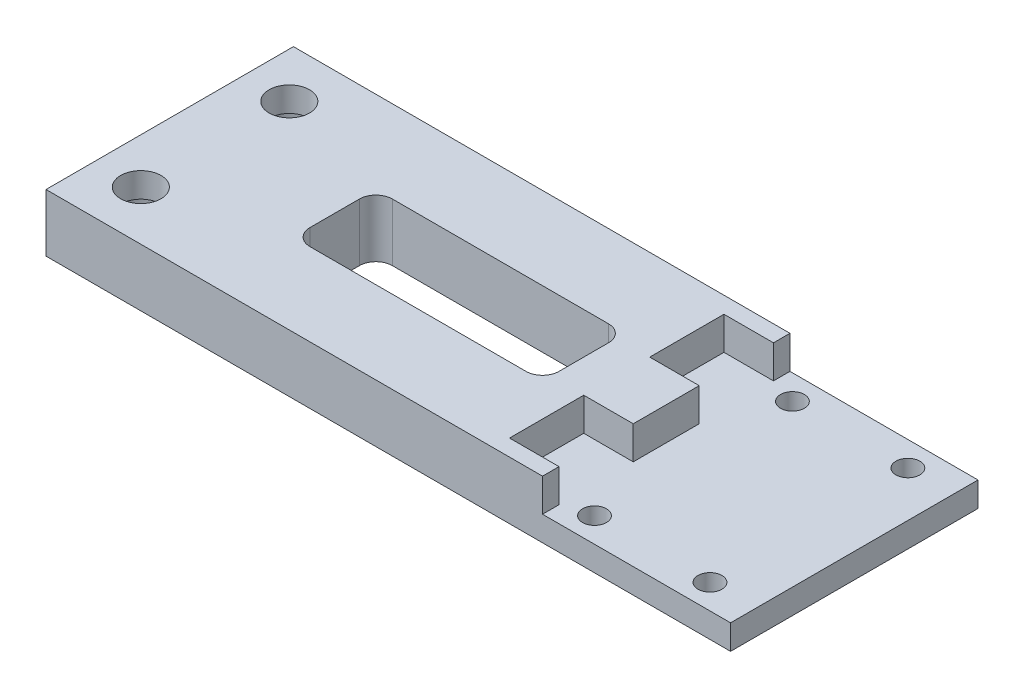
SolidWorks part; units mm, degrees
other "标注1"
sketch "草图16" plane through (-5, 0, 0) normal (0.1182, -0.9126, 0.3914) x (-0.9865, -0.0628, 0.1513)
ref_plane "前视基准面" through (0, 0, 0) normal (0, 0, 1) x (1, 0, 0)
ref_plane "上视基准面" through (0, 0, 0) normal (0, 1, 0) x (1, 0, 0)
ref_plane "右视基准面" through (0, 0, 0) normal (1, 0, 0) x (0, 0, -1)
other "Configuration Table"
sketch "草图1" plane through (0, 0, 0) normal (0, 1, 0) x (1, 0, 0)
  line L1 (0, 0) -> (-88, 0)
  line L2 (0, 0) -> (0, 30)
  line L3 (0, 30) -> (-88, 30)
  line L4 (-88, 0) -> (-88, 30)
  dimension "D1" = 88
  dimension "D2" = 30
extrude "凸台-拉伸1" add sketch "草图1" along normal blind 3
sketch "草图2" plane through (0, 3, 0) normal (0, 1, 0) x (1, 0, 0)
  line L0 (-88, 0) -> (0, 0) construction
  line L1 (0, 30) -> (-27.8, 30)
  line L2 (0, 30) -> (0, 0)
  line L3 (0, 0) -> (-27.8, 0)
  line L4 (-27.8, 30) -> (-27.8, 0)
  dimension "D1" = 27.8
extrude "切除-拉伸1" cut sketch "草图2" against normal blind 1
sketch "草图3" plane through (0, 2, 0) normal (0, 1, 0) x (1, 0, 0)
  line L0 (-27.5, 30) -> (-27.5, 27) construction
  line L3 (-27.5, 27) -> (-24.5, 27) construction
  line L4 (-24.5, 27) -> (-24.5, 3) construction
  line L5 (-24.5, 3) -> (-10.5, 3) construction
  line L6 (-10.5, 3) -> (-10.5, 27) construction
  circle A4 centre (-24.5, 27) radius 1.45
  circle A5 centre (-24.5, 3) radius 1.45
  circle A6 centre (-10.5, 3) radius 1.45
  circle A7 centre (-10.5, 27) radius 1.45
  dimension "D6" = 2.9
  dimension "D1" = 3
  dimension "D2" = 3
  dimension "D3" = 24
  dimension "D4" = 14
  dimension "D5" = 24
extrude "切除-拉伸2" cut sketch "草图3" against normal blind 11
sketch "草图4" plane through (0, 3, 0) normal (0, 1, 0) x (1, 0, 0)
  line L0 (-88, 24) -> (-82.5, 24) construction
  line L2 (-27.8, 30) -> (-88, 30) construction
  line L3 (-88, 15) -> (-85.0043, 15) construction
  line L4 (-88, 30) -> (-88, 0) construction
  circle A0 centre (-82.5, 24) radius 2.45
  circle A1 centre (-82.5, 6) radius 2.45
  dimension "D2" = 4.9
  dimension "D1" = 5.5
  dimension "D3" = 6
extrude "切除-拉伸4" cut sketch "草图4" against normal blind 11
sketch "草图5" plane through (0, 3, 0) normal (0, 1, 0) x (1, 0, 0)
  line L0 (-88, 0) -> (-27.8, 0) construction
  line L1 (-68, 20) -> (-37.8, 20)
  line L2 (-68, 20) -> (-68, 10)
  line L3 (-68, 10) -> (-37.8, 10)
  line L4 (-37.8, 20) -> (-37.8, 10)
  line L5 (-27.8, 30) -> (-88, 30) construction
  line L6 (-27.8, 30) -> (-27.8, 0) construction
  line L7 (-88, 30) -> (-88, 0) construction
  dimension "D1" = 10
  dimension "D2" = 10
  dimension "D3" = 10
  dimension "D4" = 20
extrude "切除-拉伸5" cut sketch "草图5" against normal blind 11
fillet "圆角1" radius 2 4 edges at (-68, 1.5, -10) (-37.8, 1.5, -10) (-37.8, 1.5, -20) (-68, 1.5, -20)
sketch "草图6" plane through (0, 0, 0) normal (0, -1, 0) x (1, 0, 0)
  line L0 (0, -30) -> (-88, -30) construction
  line L1 (0, 0) -> (-5, 0)
  line L2 (0, 0) -> (0, -30)
  line L3 (0, -30) -> (-5, -30)
  line L4 (-5, 0) -> (-5, -30)
  dimension "D1" = 5
extrude "切除-拉伸6" cut sketch "草图6" against normal blind 10
sketch "草图7" plane through (0, 2, 0) normal (0, 1, 0) x (1, 0, 0)
  line L4 (-27.8, 0) -> (-5, 0)
  line L5 (-5, 0) -> (-5, 30)
  line L6 (-5, 30) -> (-27.8, 30)
  line L7 (-27.8, 30) -> (-27.8, 0)
  line L8 (-27.8, 0) -> (-5, 0)
  line L9 (-5, 0) -> (-5, 30)
  line L10 (-5, 30) -> (-27.8, 30)
  line L11 (-27.8, 30) -> (-27.8, 0)
  circle A0 centre (-24.5, 27) radius 1.45 construction
  circle A1 centre (-10.5, 3) radius 1.45 construction
  circle A2 centre (-10.5, 3) radius 1.45
  circle A3 centre (-24.5, 27) radius 1.45
  circle A4 centre (-10.5, 27) radius 1.45 construction
  circle A5 centre (-24.5, 3) radius 1.45 construction
  circle A6 centre (-10.5, 27) radius 1.45
  circle A7 centre (-24.5, 3) radius 1.45
  dimension "D1" = 0
sketch "草图9" plane through (0, 3, 0) normal (0, 1, 0) x (1, 0, 0)
  line L0 (-39.8, 20) -> (-66, 20) construction
  line L1 (-66, 10) -> (-39.8, 10) construction
  line L2 (-68, 18) -> (-68, 12) construction
  line L3 (-37.8, 12) -> (-37.8, 18) construction
  line L4 (-27.8, 0) -> (-27.8, 30)
  line L5 (-27.8, 30) -> (-88, 30)
  line L6 (-88, 30) -> (-88, 0)
  line L7 (-88, 0) -> (-27.8, 0)
  line L8 (-27.8, 0) -> (-27.8, 30)
  line L9 (-27.8, 30) -> (-88, 30)
  line L10 (-88, 30) -> (-88, 0)
  line L11 (-88, 0) -> (-27.8, 0)
  line L12 (-37.8, 12) -> (-37.8, 18)
  line L13 (-68, 18) -> (-68, 12)
  line L14 (-66, 10) -> (-39.8, 10)
  line L15 (-39.8, 20) -> (-66, 20)
  circle A0 centre (-82.5, 24) radius 2.45 construction
  circle A1 centre (-82.5, 6) radius 2.45 construction
  arc A2 (-37.8, 18) -> (-39.8, 20) centre (-39.8, 18) ccw construction
  arc A3 (-66, 20) -> (-68, 18) centre (-66, 18) ccw construction
  arc A4 (-68, 12) -> (-66, 10) centre (-66, 12) ccw construction
  arc A5 (-39.8, 10) -> (-37.8, 12) centre (-39.8, 12) ccw construction
  arc A6 (-39.8, 10) -> (-37.8, 12) centre (-39.8, 12) ccw
  arc A7 (-68, 12) -> (-66, 10) centre (-66, 12) ccw
  arc A8 (-66, 20) -> (-68, 18) centre (-66, 18) ccw
  arc A9 (-37.8, 18) -> (-39.8, 20) centre (-39.8, 18) ccw
  circle A10 centre (-82.5, 6) radius 2.45
  circle A11 centre (-82.5, 24) radius 2.45
  dimension "D1" = 0
extrude "凸台-拉伸4" add sketch "草图9" along normal blind 4
extrude "凸台-拉伸5" add sketch "草图7" along normal blind 1
sketch "草图11" plane through (-27.8, 0, 0) normal (1, 0, 0) x (0, 0, -1)
  line L0 (0, 3) -> (30, 3) construction
  line L6 (30, 3) -> (15, 3)
  line L7 (30, 3) -> (30, 7)
  line L8 (30, 7) -> (15, 7)
  line L9 (15, 3) -> (15, 7)
extrude "切除-拉伸8" cut sketch "草图11" against normal blind 6
sketch "草图12" plane through (-33.8, 0, 0) normal (1, 0, 0) x (0, 0, -1)
  line L0 (15, 3) -> (30, 3) construction
  line L1 (30, 7) -> (28, 7)
  line L2 (30, 7) -> (30, 3)
  line L3 (30, 3) -> (28, 3)
  line L4 (28, 7) -> (28, 3)
  dimension "D1" = 2
extrude "凸台-拉伸6" add sketch "草图12" along normal blind 6
sketch "草图13" plane through (0, 0, -15) normal (0, 0, -1) x (-1, 0, 0)
  line L4 (27.8, 7) -> (27.8, 3)
  line L5 (27.8, 3) -> (33.8, 3)
  line L6 (33.8, 3) -> (33.8, 7)
  line L7 (33.8, 7) -> (27.8, 7)
  line L8 (27.8, 7) -> (27.8, 3)
  line L9 (27.8, 3) -> (33.8, 3)
  line L10 (33.8, 3) -> (33.8, 7)
  line L11 (33.8, 7) -> (27.8, 7)
  dimension "D1" = 0
extrude "凸台-拉伸7" add sketch "草图13" along normal blind 4
sketch "草图14" plane through (0, 0, 0) normal (0, -1, 0) x (1, 0, 0)
  circle A0 centre (-82.5, -6) radius 4
  circle A1 centre (-82.5, -24) radius 4
  dimension "D1" = 8
  dimension "D2" = 8
extrude "切除-拉伸9" cut sketch "草图14" against normal blind 4
sketch "草图15" plane through (-27.8, 0, 0) normal (1, 0, 0) x (0, 0, -1)
  line L0 (0, 7) -> (19, 7) construction
  line L1 (2, 7) -> (11, 7)
  line L2 (2, 7) -> (2, 3)
  line L3 (2, 3) -> (11, 3)
  line L4 (11, 7) -> (11, 3)
  line L5 (19, 3) -> (0, 3) construction
  line L6 (0, 3) -> (0, 7) construction
  dimension "D1" = 9
  dimension "D2" = 2
extrude "切除-拉伸10" cut sketch "草图15" against normal up to surface (6 mm away) up to face at (-33.8, 5, -23.5)
